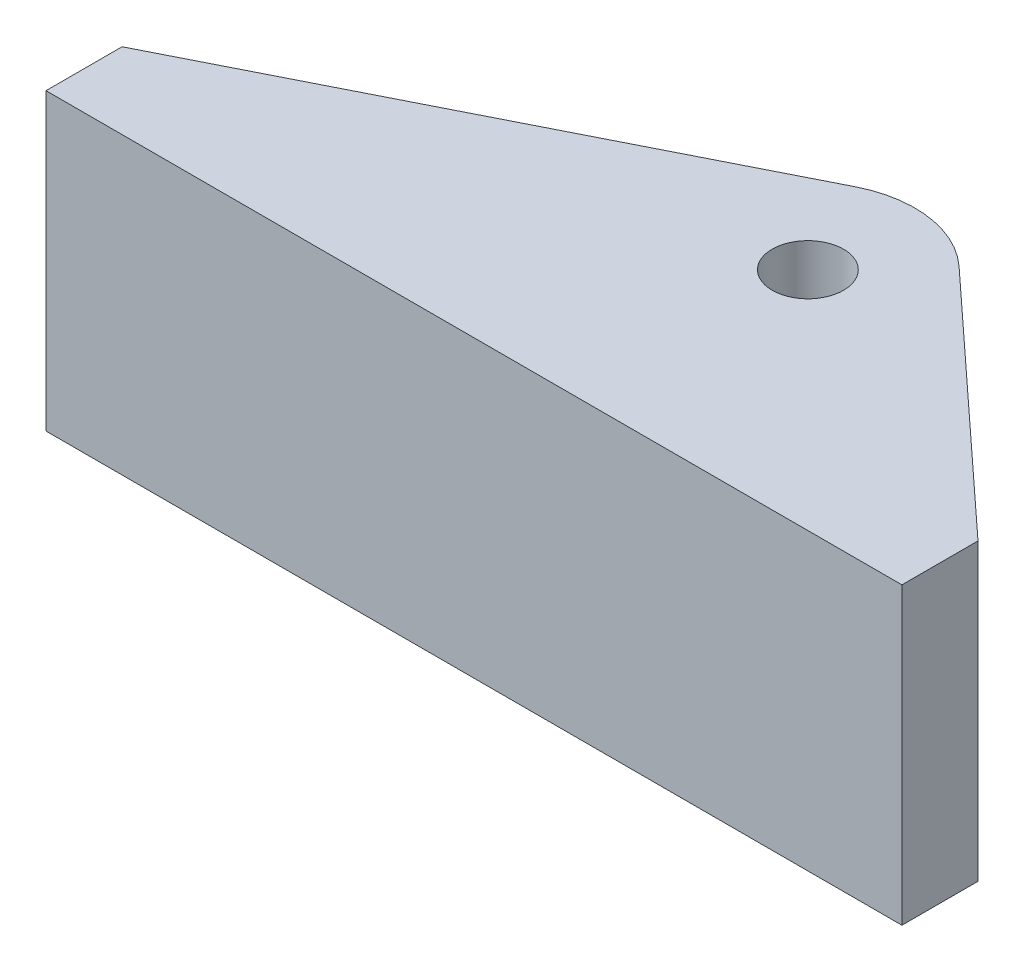
SolidWorks part; units mm, degrees
material "Cast Alloy Steel"
ref_plane "Front Plane" through (0, 0, 0) normal (0, 0, 1) x (1, 0, 0)
ref_plane "Top Plane" through (0, 0, 0) normal (0, 1, 0) x (1, 0, 0)
ref_plane "Right Plane" through (0, 0, 0) normal (1, 0, 0) x (0, 0, -1)
sketch "Sketch1" plane through (0, 0, 0) normal (0, 1, 0) x (1, 0, 0)
  line L0 (0, 5.08) -> (32.5791, 21.4634)
  line L1 (0, 0) -> (57.15, 0)
  line L2 (0, 0) -> (0, 5.08)
  line L4 (57.15, 0) -> (57.15, 5.08)
  line L5 (57.15, 5.08) -> (40.6349, 20.3297)
  circle A0 centre (35.7886, 15.0813) radius 2.3812
  arc A1 (40.6349, 20.3297) -> (32.5791, 21.4634) centre (35.7886, 15.0813) ccw
  dimension "D1" = 57.15
  dimension "D2" = 4.7625
  dimension "D5" = 21.3614
  dimension "D6" = 4.7625
  dimension "D3" = 15.0812
  dimension "D4" = 5.08
extrude "Boss-Extrude1" add sketch "Sketch1" against normal blind 19.685
